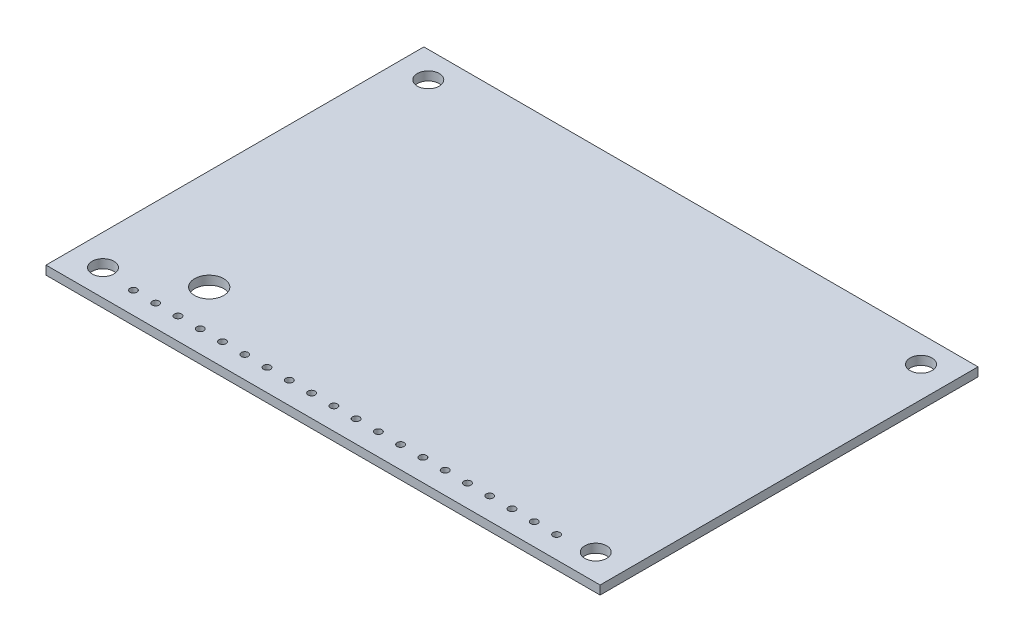
SolidWorks part; units mm, degrees
ref_plane "Front" through (0, 0, 0) normal (0, 0, 1) x (1, 0, 0)
ref_plane "Top" through (0, 0, 0) normal (0, 1, 0) x (1, 0, 0)
ref_plane "Right" through (0, 0, 0) normal (1, 0, 0) x (0, 0, -1)
sketch "Sketch1" plane through (0, 0, 0) normal (0, 1, 0) x (1, 0, 0)
  line L1 (0, 0) -> (63.2, 0)
  line L2 (0, 0) -> (0, 43.1)
  line L3 (0, 43.1) -> (63.2, 43.1)
  line L4 (63.2, 0) -> (63.2, 43.1)
  dimension "D1" = 63.2
  dimension "D2" = 43.1
extrude "Boss-Extrude1" add sketch "Sketch1" along normal blind 1
sketch "Sketch2" plane through (0, 1, 0) normal (0, 1, 0) x (1, 0, 0)
  line L0 (63.2, 43.1) -> (0, 43.1) construction
  line L1 (0, 0) -> (63.2, 0) construction
  line L2 (0, 43.1) -> (0, 0) construction
  line L3 (63.2, 0) -> (63.2, 43.1) construction
  circle A0 centre (3.5, 40.1) radius 1.25
  circle A1 centre (59.7, 40.1) radius 1.25
  circle A2 centre (59.7, 3) radius 1.25
  circle A3 centre (3.5, 3) radius 1.25
  dimension "D1" = 3
  dimension "D2" = 3
  dimension "D7" = 3.5
  dimension "D8" = 3.5
  dimension "D9" = 2.5
  dimension "D10" = 2.5
  dimension "D11" = 2.5
  dimension "D12" = 2.5
  dimension "D3" = 3
  dimension "D4" = 3
  dimension "D5" = 3.5
  dimension "D6" = 3.5
extrude "Cut-Extrude1" cut sketch "Sketch2" against normal up to next
sketch "Sketch3" plane through (0, 1, 0) normal (0, 1, 0) x (1, 0, 0)
  line L0 (0, 43.1) -> (0, 0) construction
  line L1 (0, 0) -> (63.2, 0) construction
  circle A0 centre (7.47, 2.5) radius 0.4
  circle A1 centre (10.01, 2.5) radius 0.4
  circle A2 centre (12.55, 2.5) radius 0.4
  circle A3 centre (15.09, 2.5) radius 0.4
  circle A4 centre (17.63, 2.5) radius 0.4
  circle A5 centre (20.17, 2.5) radius 0.4
  circle A6 centre (22.71, 2.5) radius 0.4
  circle A7 centre (25.25, 2.5) radius 0.4
  circle A8 centre (27.79, 2.5) radius 0.4
  circle A9 centre (30.33, 2.5) radius 0.4
  circle A10 centre (32.87, 2.5) radius 0.4
  circle A11 centre (35.41, 2.5) radius 0.4
  circle A12 centre (37.95, 2.5) radius 0.4
  circle A13 centre (40.49, 2.5) radius 0.4
  circle A14 centre (43.03, 2.5) radius 0.4
  circle A15 centre (45.57, 2.5) radius 0.4
  circle A16 centre (48.11, 2.5) radius 0.4
  circle A17 centre (50.65, 2.5) radius 0.4
  circle A18 centre (53.19, 2.5) radius 0.4
  circle A19 centre (55.73, 2.5) radius 0.4
  dimension "D1" = 7.47
  dimension "D2" = 0.8
  dimension "D3" = 2.5
  dimension "D4" = 20
extrude "Cut-Extrude2" cut sketch "Sketch3" against normal up to next
sketch "Sketch25" plane through (0, 0, 0) normal (0, -1, 0) x (1, 0, 0)
  circle A0 centre (11.4785, -7.1361) radius 1.6634
extrude "Cut-Extrude18" cut sketch "Sketch25" against normal up to next
